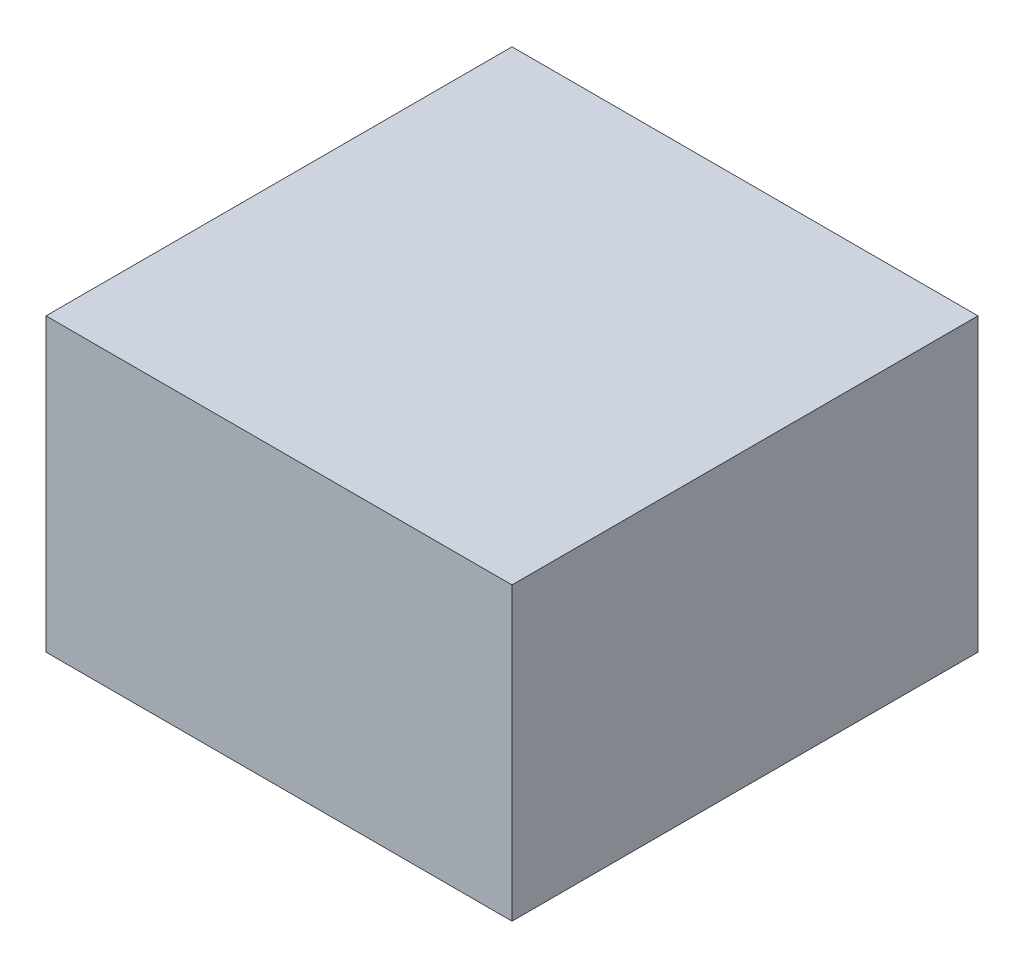
SolidWorks part; units mm, degrees
ref_plane "Front Plane" through (0, 0, 0) normal (0, 0, 1) x (1, 0, 0)
ref_plane "Top Plane" through (0, 0, 0) normal (0, 1, 0) x (1, 0, 0)
ref_plane "Right Plane" through (0, 0, 0) normal (1, 0, 0) x (0, 0, -1)
sketch "Sketch1" plane through (0, 0, 0) normal (0, 1, 0) x (1, 0, 0)
  line L1 (-40, 40) -> (40, 40)
  line L2 (-40, 40) -> (-40, -40)
  line L3 (-40, -40) -> (40, -40)
  line L4 (40, 40) -> (40, -40)
  line L5 (-40, 40) -> (40, -40) construction
  line L6 (-40, -40) -> (40, 40) construction
  point P0 (0, 0)
  dimension "D1" = 80
extrude "Boss-Extrude1" add sketch "Sketch1" along normal blind 50
